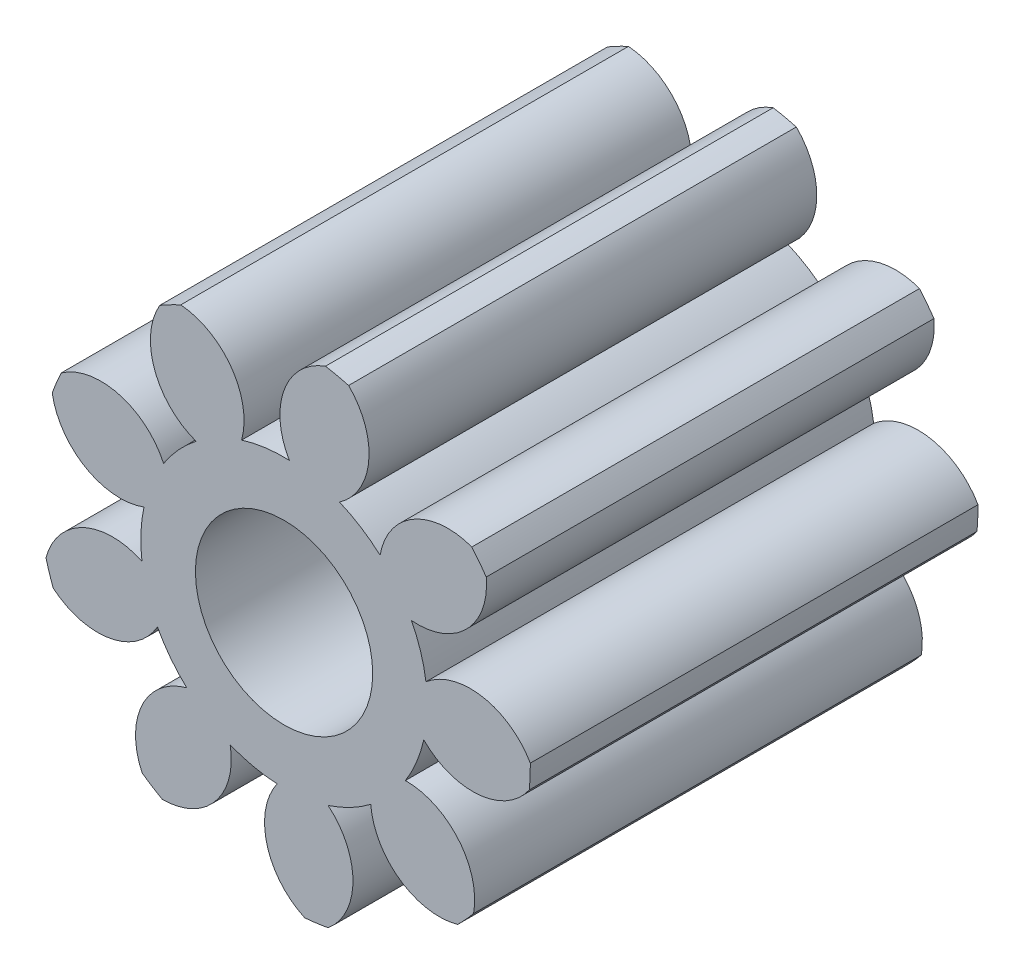
SolidWorks part; units mm, degrees
ref_plane "Alzado" through (0, 0, 0) normal (0, 0, 1) x (1, 0, 0)
ref_plane "Planta" through (0, 0, 0) normal (0, 1, 0) x (1, 0, 0)
ref_plane "Vista lateral" through (0, 0, 0) normal (1, 0, 0) x (0, 0, -1)
sketch "Croquis1" plane through (0, 0, 0) normal (0, 0, 1) x (1, 0, 0)
  circle A0 centre (0, 0) radius 2.75
  circle A1 centre (0, 0) radius 0.99
  dimension "D1" = 5.5
  dimension "D2" = 1.98
extrude "Saliente-Extruir1" add sketch "Croquis1" along normal blind 5
sketch "Croquis2" plane through (0, 0, 5) normal (0, 0, 1) x (1, 0, 0)
  line L0 (0, 0) -> (0, 3.7663) construction
  line L1 (0, 3.7663) -> (0, 0) construction
  line L2 (0, 0) -> (1.3239, 3.6374) construction
  line L3 (0, 2.25) -> (0.7231, 1.9868) construction
  line L4 (0, 0) -> (-0.5, 3.7663) construction
  circle A0 centre (0, 0) radius 2.75
  circle A1 centre (0, 0) radius 1.6
  circle A2 centre (0, 0) radius 2.25
  circle A3 centre (0.7231, 1.9868) radius 0.7695
  circle A4 centre (-1.2165, 1.7293) radius 0.7695
  dimension "D1" = 5.5
  dimension "D2" = 3.2
  dimension "D3" = 4.5
  dimension "D4" = 20
  dimension "D5" = 0.5
extrude "Cortar-Extruir1" cut sketch "Croquis2" against normal blind 5 contours A0 A4 A2 A3 | A2 A4 A1 A3
pattern_circular "MatrizC2" count 9 over 360 about axis through (0, 0, 0) along (0, 0, 1) of "Cortar-Extruir1"
